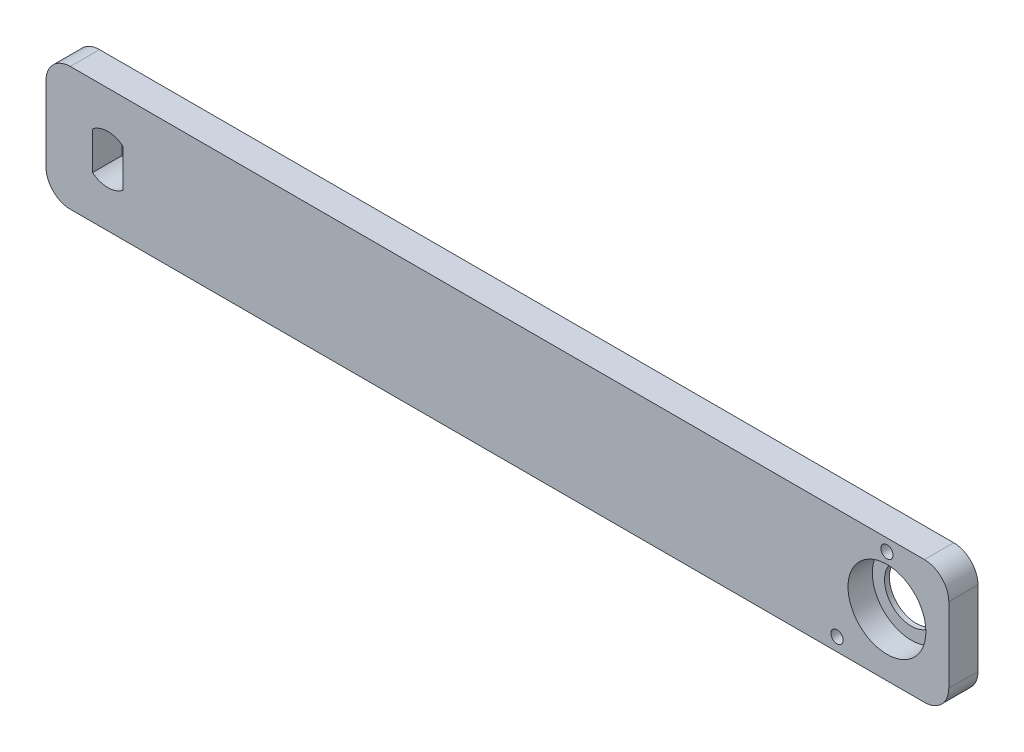
SolidWorks part; units mm, degrees
ref_plane "Alzado" through (0, 0, 0) normal (0, 0, 1) x (1, 0, 0)
ref_plane "Planta" through (0, 0, 0) normal (0, 1, 0) x (1, 0, 0)
ref_plane "Vista lateral" through (0, 0, 0) normal (1, 0, 0) x (0, 0, -1)
sketch "Croquis1" plane through (0, 0, 0) normal (0, 0, 1) x (1, 0, 0)
  line L0 (0, 0) -> (320, 0) construction
  line L2 (-6.28, -7.7821) -> (-6.28, 7.7821)
  line L3 (-25.4, 25.4) -> (345.4, 25.4)
  line L4 (6.28, -7.7821) -> (6.28, 7.7821)
  line L5 (-6.28, -7.7821) -> (6.28, 7.7821) construction
  line L6 (-6.28, 7.7821) -> (6.28, -7.7821) construction
  line L7 (-25.4, 25.4) -> (-25.4, -25.4)
  line L8 (-25.4, -25.4) -> (345.4, -25.4)
  line L9 (345.4, 25.4) -> (345.4, -25.4)
  arc A0 (-6.28, -7.7821) -> (6.28, -7.7821) centre (0, 0) ccw
  arc A1 (6.28, 7.7821) -> (-6.28, 7.7821) centre (0, 0) ccw
  circle A2 centre (320, 0) radius 11
  dimension "D1" = 20
  dimension "D4" = 22
  dimension "D9" = 25.4
  dimension "D10" = 25.4
  dimension "D2" = 12.56
  dimension "D3" = 320
  dimension "D7" = 50.8
  dimension "D8" = 25.4
extrude "Saliente-Extruir1" add sketch "Croquis1" along normal blind 12
fillet "Redondeo1" radius 10 4 edges at (345.4, -25.4, 6) (345.4, 25.4, 6) (-25.4, -25.4, 6) (-25.4, 25.4, 6)
sketch "Croquis4" plane through (0, 0, 12) normal (0, 0, 1) x (1, 0, 0)
  circle A0 centre (320, 0) radius 16
  dimension "D1" = 32
extrude "Cortar-Extruir3" cut sketch "Croquis4" against normal blind 10
sketch "Croquis6" plane through (0, 0, 12) normal (0, 0, 1) x (1, 0, 0)
  line L0 (320, 16) -> (320, 25) construction
  circle A0 centre (320, 0) radius 25 construction
  circle A1 centre (320, 0) radius 16 construction
  circle A2 centre (320, 20.5) radius 2.5
  circle A3 centre (360.5, 0) radius 2.5
  circle A4 centre (340, -40.5) radius 2.5
  circle A5 centre (299.5, -20) radius 2.5
  point P17 (330, -10)
  dimension "D1" = 50
  dimension "D2" = 32
  dimension "D4" = 5
  dimension "D3" = 9
  dimension "D5" = 4
extrude "Cortar-Extruir4" cut sketch "Croquis6" against normal through all
